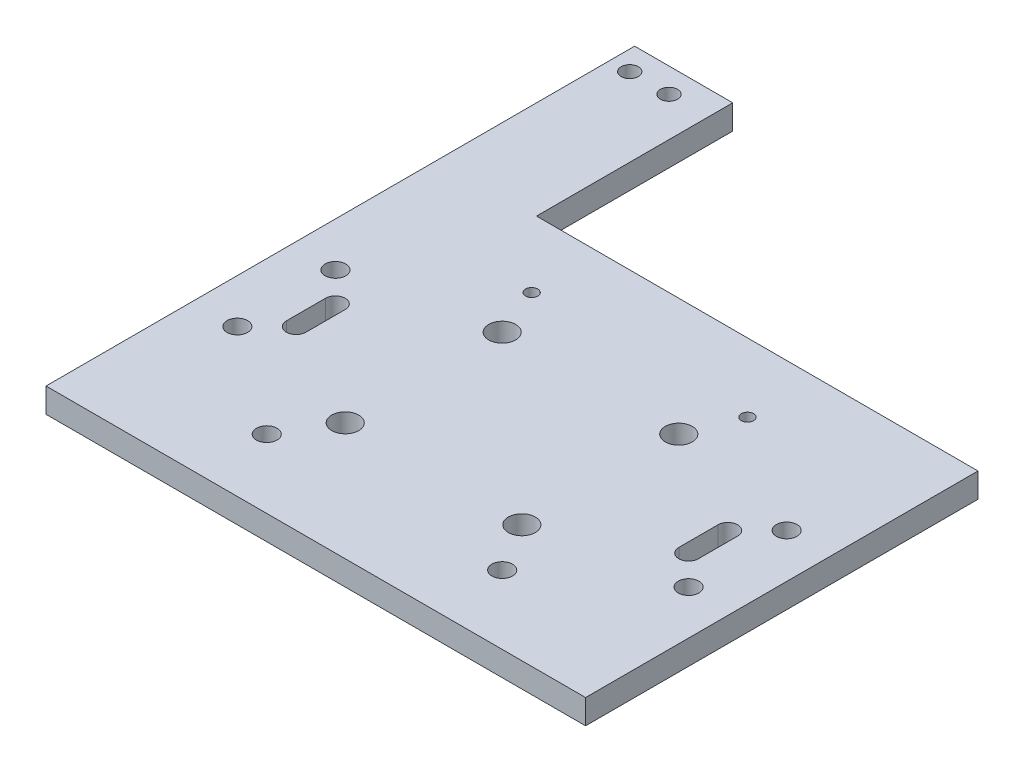
SolidWorks part; units mm, degrees
material "6061-T6 (SS)"
ref_plane "Frontal Plane" through (0, 0, 0) normal (0, 0, 1) x (1, 0, 0)
ref_plane "Horizontal Plane" through (0, 0, 0) normal (0, 1, 0) x (1, 0, 0)
ref_plane "Profile Plane" through (0, 0, 0) normal (1, 0, 0) x (0, 0, -1)
sketch "Sketch1" plane through (0, 0, 0) normal (0, 1, 0) x (1, 0, 0)
  line L1 (-55, -40) -> (55, -40)
  line L2 (-55, -40) -> (-55, 40)
  line L3 (-55, 40) -> (55, 40)
  line L4 (55, -40) -> (55, 40)
  line L5 (-55, -40) -> (55, 40) construction
  line L6 (-55, 40) -> (55, -40) construction
  circle A0 centre (-18, 16) radius 2.75
  circle A1 centre (18, 16) radius 2.75
  circle A2 centre (18, -16) radius 2.75
  circle A3 centre (-18, -16) radius 2.75
  circle A4 centre (-22, 26) radius 1.25
  circle A5 centre (22, 26) radius 1.25
  circle A6 centre (-24, -26) radius 2.1
  circle A7 centre (24, -26) radius 2.1
  point P0 (0, 0)
  dimension "D3" = 5.5
  dimension "D11" = 2.5
  dimension "D12" = 4.2
  dimension "D1" = 110
  dimension "D2" = 80
  dimension "D4" = 32
  dimension "D5" = 16
  dimension "D6" = 36
  dimension "D7" = 18
  dimension "D8" = 44
  dimension "D9" = 22
  dimension "D10" = 10
  dimension "D13" = 10
  dimension "D14" = 48
  dimension "D15" = 24
extrude "Boss-Extrude1" add sketch "Sketch1" along normal blind 5
sketch "Sketch2" plane through (0, 5, 0) normal (0, 1, 0) x (1, 0, 0)
  line L3 (-40, 4) -> (-40, -4) construction
  line L9 (-55, 40) -> (-55, -40) construction
  line L14 (-38, 4) -> (-38, -4)
  line L15 (55, -40) -> (55, 40) construction
  line L24 (-42, 4) -> (-42, -4)
  line L25 (40, 4) -> (40, -4) construction
  line L26 (42, 4) -> (42, -4)
  line L27 (38, 4) -> (38, -4)
  arc A16 (-38, 4) -> (-42, 4) centre (-40, 4) ccw
  arc A17 (-42, -4) -> (-38, -4) centre (-40, -4) ccw
  arc A18 (42, 4) -> (38, 4) centre (40, 4) ccw
  arc A19 (38, -4) -> (42, -4) centre (40, -4) ccw
  circle A28 centre (-46, 10) radius 2.1
  circle A29 centre (-46, -10) radius 2.1
  circle A30 centre (46, -10) radius 2.1
  circle A31 centre (46, 10) radius 2.1
  point P12 (-38.5, 12)
  point P26 (-40, 0)
  point P33 (40, 0)
  point P50 (-38.5, -12)
  dimension "D1" = 15
  dimension "D9" = 9
  dimension "D7" = 2
  dimension "D4" = 10
  dimension "D8" = 4.2
  dimension "D2" = 15
  dimension "D3" = 9
  dimension "D5" = 10
  dimension "D6" = 8
extrude "Cut-Extrude1" cut sketch "Sketch2" against normal through all
thread "Thread1" [suppressed] pitch 0.5 start angle 0, offset 0, length 0, pitch 0.5, diameter 2.5
ref_plane "Plane1" through (20.75, 5, -26) normal (0, 0, 1) x (-1, 0, 0)
sketch "Thread Profile1" plane through (20.75, 5, -26) normal (0, 0, 1) x (-1, 0, 0)
  line L0 (0, 0) -> (0, 0.5) construction
  line L1 (0, 0) -> (0.2706, 0.1562)
  line L2 (0.2706, 0.1562) -> (0.2706, 0.2187)
  line L3 (0.2706, 0.2187) -> (0, 0.375)
  line L4 (0.2706, 0.1875) -> (0, 0.1875) construction
  line L11 (0, 0) -> (0, 0.375)
  point P2 (0, 0)
  dimension "Pitch" = 0.5
  dimension "Profile_Angle" = 60
  dimension "Profile_Land" = 0.0625
  dimension "Profile_Height" = 0.2706
pattern_linear "LPattern1" [suppressed] count 2 spacing 44
thread "Thread2" [suppressed] pitch 0.8 start angle 0, offset 0, length 0, pitch 0.8, diameter 4.2
ref_plane "Plane2" through (21.9, 5, 26) normal (0, 0, 1) x (-1, 0, 0)
sketch "Thread Profile2" plane through (21.9, 5, 26) normal (0, 0, 1) x (-1, 0, 0)
  line L0 (0, 0) -> (0, 0.8) construction
  line L1 (0, 0) -> (0.433, 0.25)
  line L2 (0.433, 0.25) -> (0.433, 0.35)
  line L3 (0.433, 0.35) -> (0, 0.6)
  line L4 (0.433, 0.3) -> (0, 0.3) construction
  line L11 (0, 0) -> (0, 0.6)
  point P2 (0, 0)
  dimension "Pitch" = 0.8
  dimension "Profile_Angle" = 60
  dimension "Profile_Land" = 0.1
  dimension "Profile_Height" = 0.433
thread "Thread3" [suppressed] pitch 0.8 start angle 0, offset 0, length 0, pitch 0.8, diameter 4.2
ref_plane "Plane3" through (-26.1, 5, 26) normal (0, 0, 1) x (-1, 0, 0)
sketch "Thread Profile3" plane through (-26.1, 5, 26) normal (0, 0, 1) x (-1, 0, 0)
  line L0 (0, 0) -> (0, 0.8) construction
  line L1 (0, 0) -> (0.433, 0.25)
  line L2 (0.433, 0.25) -> (0.433, 0.35)
  line L3 (0.433, 0.35) -> (0, 0.6)
  line L4 (0.433, 0.3) -> (0, 0.3) construction
  line L11 (0, 0) -> (0, 0.6)
  point P2 (0, 0)
  dimension "Pitch" = 0.8
  dimension "Profile_Angle" = 60
  dimension "Profile_Land" = 0.1
  dimension "Profile_Height" = 0.433
thread "Thread4" [suppressed] pitch 0.8 start angle 0, offset 0, length 0, pitch 0.8, diameter 4.2
ref_plane "Plane4" through (43.9, 5, -10) normal (0, 0, 1) x (-1, 0, 0)
sketch "Thread Profile4" plane through (43.9, 5, -10) normal (0, 0, 1) x (-1, 0, 0)
  line L0 (0, 0) -> (0, 0.8) construction
  line L1 (0, 0) -> (0.433, 0.25)
  line L2 (0.433, 0.25) -> (0.433, 0.35)
  line L3 (0.433, 0.35) -> (0, 0.6)
  line L4 (0.433, 0.3) -> (0, 0.3) construction
  line L11 (0, 0) -> (0, 0.6)
  point P2 (0, 0)
  dimension "Pitch" = 0.8
  dimension "Profile_Angle" = 60
  dimension "Profile_Land" = 0.1
  dimension "Profile_Height" = 0.433
thread "Thread5" [suppressed] pitch 0.8 start angle 0, offset 0, length 0, pitch 0.8, diameter 4.2
ref_plane "Plane5" through (43.9, 5, 10) normal (0, 0, 1) x (-1, 0, 0)
sketch "Thread Profile5" plane through (43.9, 5, 10) normal (0, 0, 1) x (-1, 0, 0)
  line L0 (0, 0) -> (0, 0.8) construction
  line L1 (0, 0) -> (0.433, 0.25)
  line L2 (0.433, 0.25) -> (0.433, 0.35)
  line L3 (0.433, 0.35) -> (0, 0.6)
  line L4 (0.433, 0.3) -> (0, 0.3) construction
  line L11 (0, 0) -> (0, 0.6)
  point P2 (0, 0)
  dimension "Pitch" = 0.8
  dimension "Profile_Angle" = 60
  dimension "Profile_Land" = 0.1
  dimension "Profile_Height" = 0.433
thread "Thread6" [suppressed] pitch 0.8 start angle 0, offset 0, length 0, pitch 0.8, diameter 4.2
ref_plane "Plane6" through (-48.1, 5, -10) normal (0, 0, 1) x (-1, 0, 0)
sketch "Thread Profile6" plane through (-48.1, 5, -10) normal (0, 0, 1) x (-1, 0, 0)
  line L0 (0, 0) -> (0, 0.8) construction
  line L1 (0, 0) -> (0.433, 0.25)
  line L2 (0.433, 0.25) -> (0.433, 0.35)
  line L3 (0.433, 0.35) -> (0, 0.6)
  line L4 (0.433, 0.3) -> (0, 0.3) construction
  line L11 (0, 0) -> (0, 0.6)
  point P2 (0, 0)
  dimension "Pitch" = 0.8
  dimension "Profile_Angle" = 60
  dimension "Profile_Land" = 0.1
  dimension "Profile_Height" = 0.433
thread "Thread7" [suppressed] pitch 0.8 start angle 0, offset 0, length 0, pitch 0.8, diameter 4.2
ref_plane "Plane7" through (-48.1, 5, 10) normal (0, 0, 1) x (-1, 0, 0)
sketch "Thread Profile7" plane through (-48.1, 5, 10) normal (0, 0, 1) x (-1, 0, 0)
  line L0 (0, 0) -> (0, 0.8) construction
  line L1 (0, 0) -> (0.433, 0.25)
  line L2 (0.433, 0.25) -> (0.433, 0.35)
  line L3 (0.433, 0.35) -> (0, 0.6)
  line L4 (0.433, 0.3) -> (0, 0.3) construction
  line L11 (0, 0) -> (0, 0.6)
  point P2 (0, 0)
  dimension "Pitch" = 0.8
  dimension "Profile_Angle" = 60
  dimension "Profile_Land" = 0.1
  dimension "Profile_Height" = 0.433
sketch "Sketch7" plane through (0, 0, 0) normal (0, 1, 0) x (1, 0, 0)
  line L0 (-55, 40) -> (-55, 80)
  line L1 (-55, 80) -> (-35, 80)
  line L2 (-35, 80) -> (-35, 40)
  line L3 (55, 40) -> (-55, 40) construction
  line L4 (-35, 40) -> (-55, 40)
  dimension "D1" = 40
  dimension "D2" = 20
extrude "Boss-Extrude2" add sketch "Sketch7" along normal up to surface (5 mm away) up to face at (-46, 5, 12.1)
sketch "Sketch8" plane through (0, 5, 0) normal (0, 1, 0) x (1, 0, 0)
  line L0 (-51, 75) -> (-43, 75) construction
  line L1 (-55, 80) -> (-35, 80) construction
  line L2 (-47, 84) -> (-47, 66) construction
  line L3 (-55, 80) -> (-55, -40) construction
  circle A0 centre (-51, 75) radius 1.75
  circle A1 centre (-43, 75) radius 1.75
  point P11 (-47, 75)
  dimension "D2" = 3.5
  dimension "D1" = 8
  dimension "D3" = 18
  dimension "D4" = 5
  dimension "D5" = 4
extrude "Cut-Extrude2" cut sketch "Sketch8" against normal up to next
sketch "Sketch9" [suppressed] plane through (0, 0, 0) normal (0, 1, 0) x (1, 0, 0)
  line L1 (-86.1139, -12.3494) -> (-60.7139, -12.3494) construction
  line L2 (-86.1139, -12.3494) -> (-86.1139, -37.7494) construction
  line L3 (-86.1139, -37.7494) -> (-60.7139, -37.7494) construction
  line L4 (-60.7139, -12.3494) -> (-60.7139, -37.7494) construction
  line L5 (-86.1139, -12.3494) -> (-60.7139, -37.7494) construction
  line L6 (-86.1139, -37.7494) -> (-60.7139, -12.3494) construction
  point P0 (-73.4139, -25.0494)
  dimension "D1" = 25.4
equation "\"BaseL\"= 6ft"
equation "\"BaseW\"= 5.5in"
equation "\"BaseThickness\"= 1in"
equation "\"RailGap\"= 4cm"
equation "\"SlidePlateL\"= 8cm"
equation "\"SlidePlateW\"= 11cm"
equation "\"SlidePlateThickness\"= 5mm"
equation "\"SlidePlateClearance\"= 1cm"
equation "\"BoxThickness\"= .5cm"
equation "\"BoxX\"= \"RailGap\" + 30mm"
equation "\"BoxH\"= 2cm + \"SlidePlateClearance\" + \"SlidePlateThickness\" + 3cm"
equation "\"PulleyRadius\"= 15.1mm"
equation "\"PulleyH\"= 30mm + 21.4056mm - 2.5mm"
equation "\"PulleyShaftDiameter\"= .3125in"
equation "\"PulleyShaftL\"= 4in"
equation "\"PulleyShaft2L\"= 3in"
equation "\"MotorL\"= 4.43in"
equation "\"MotorRadius\"= 1.291in"
equation "\"MotorShaftRadius\"= .15625in"
equation "\"MotorShaftL\"= 1.75in"
equation "\"HeadstoneThickness\"= 7.5mm"
equation "\"BeltL\"= 1500mm + \"80\""
equation "\"BeltThickness\"= 2.5mm"
equation "\"BeltW\"= .375in"
equation "\"BeltLockH\"= \"PulleyH\" + 19.4056mm - (\"SlidePlateThickness\" + \"SlidePlateClearance\" + 15mm + 5mm)"
equation "\"EncoderL\"= 33mm"
equation "\"EncoderRadius\"= 19mm"
equation "\"EncoderShaftRadius\"= 3mm"
equation "\"EncoderShaftL\"= 15mm"
equation "\"PendulumShaftL\"= \"100mm\" "
equation "\"PendulumShaftRadius\"= 3mm"
equation "\"RodL\"= 39in"
equation "\"RodRadius\"= 3mm"
equation "\"PillowBlockCenterH\"= \"EncoderRadius\" + 2mm"
equation "\"D1@Sketch1\"=\"SlidePlateW\""
equation "\"D2@Sketch1\"=\"SlidePlateL\""
equation "\"D1@Boss-Extrude1\"=\"SlidePlateThickness\""
